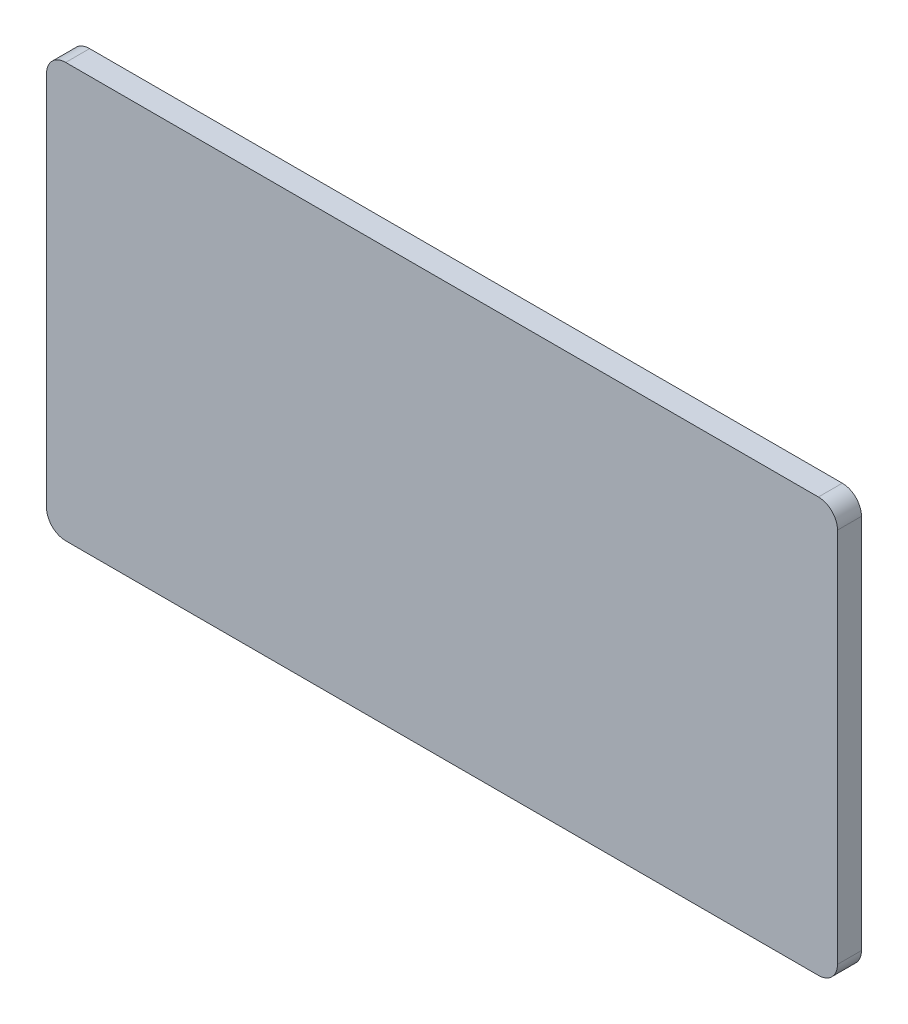
SolidWorks part; units mm, degrees
material "Custom Plastic"
ref_plane "X-Y Datum" through (0, 0, 0) normal (0, 0, 1) x (1, 0, 0)
ref_plane "X-Z Datum" through (0, 0, 0) normal (0, 1, 0) x (1, 0, 0)
ref_plane "Y-Z Datum" through (0, 0, 0) normal (1, 0, 0) x (0, 0, -1)
sketch "Sketch1" plane through (0, 0, 0) normal (0, 0, 1) x (1, 0, 0)
  line L1 (-52.5, -27.5) -> (52.5, -27.5)
  line L2 (-52.5, -27.5) -> (-52.5, 27.5)
  line L3 (-52.5, 27.5) -> (52.5, 27.5)
  line L4 (52.5, -27.5) -> (52.5, 27.5)
  line L5 (-52.5, -27.5) -> (52.5, 27.5) construction
  line L6 (-52.5, 27.5) -> (52.5, -27.5) construction
  point P0 (0, 0)
  dimension "D1" = 55
  dimension "D2" = 105
extrude "Boss-Extrude1" add sketch "Sketch1" along normal blind 3.175
fillet "Fillet1" radius 2.54 4 edges at (-52.5, -27.5, 1.5875) (-52.5, 27.5, 1.5875) (52.5, -27.5, 1.5875) (52.5, 27.5, 1.5875)
